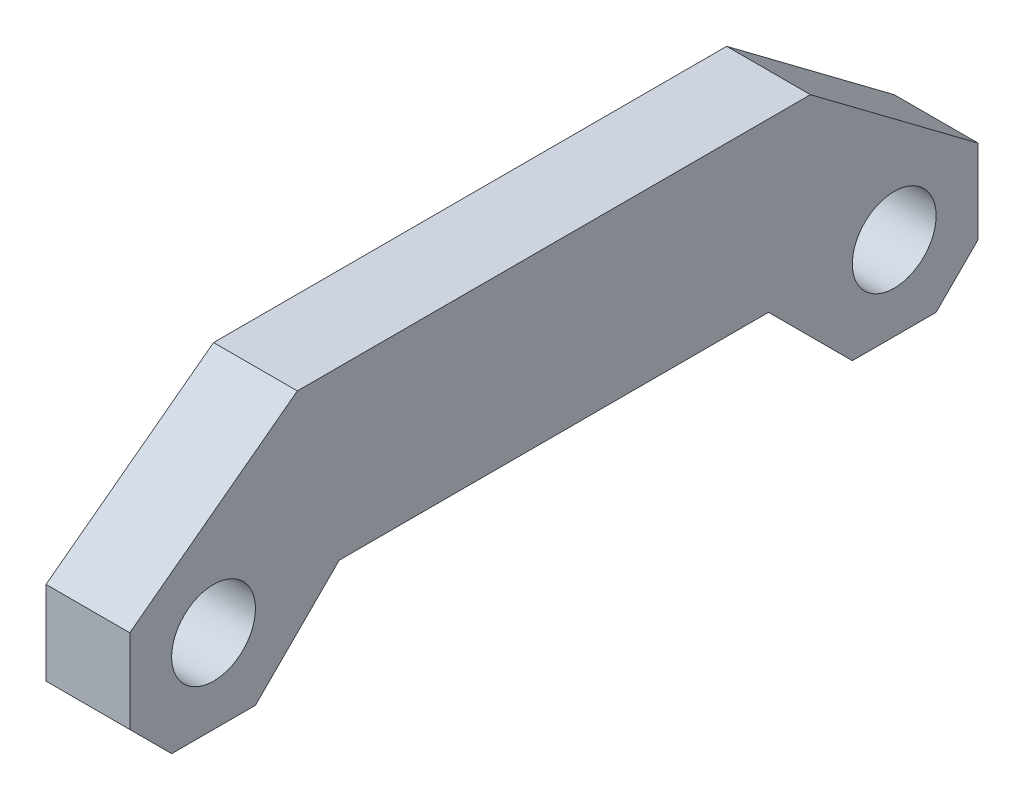
SolidWorks part; units mm, degrees
ref_plane "Front" through (0, 0, 0) normal (0, 0, 1) x (1, 0, 0)
ref_plane "Top" through (0, 0, 0) normal (0, 1, 0) x (1, 0, 0)
ref_plane "Right" through (0, 0, 0) normal (1, 0, 0) x (0, 0, -1)
sketch "Sketch1" plane through (0, 0, 0) normal (1, 0, 0) x (0, 0, -1)
  line L0 (-103.1875, 0) -> (103.1875, 0) construction
  line L1 (-128.5875, 50.8) -> (128.5875, 50.8)
  line L2 (-128.5875, 50.8) -> (-128.5875, -25.4)
  line L3 (-128.5875, -25.4) -> (128.5875, -25.4)
  line L4 (128.5875, 50.8) -> (128.5875, -25.4)
  line L5 (0, -25.4) -> (0, 50.8) construction
  circle A0 centre (-103.1875, 0) radius 12.7
  circle A1 centre (103.1875, 0) radius 12.7
  dimension "D5" = 25.4
  dimension "D1" = 25.4
  dimension "D2" = 76.2
  dimension "D3" = 206.375
  dimension "D4" = 25.4
extrude "Extrude1" add sketch "Sketch1" along normal mid plane 25.4
sketch "Sketch2" plane through (12.7, 0, 0) normal (1, 0, 0) x (0, 0, -1)
  line L0 (-90.4875, -25.4) -> (-65.0875, 0)
  line L1 (-128.5875, -25.4) -> (128.5875, -25.4) construction
  line L2 (-65.0875, 0) -> (65.0875, 0)
  line L3 (65.0875, 0) -> (90.4875, -25.4)
  line L4 (90.4875, -25.4) -> (-90.4875, -25.4)
  line L5 (0, -25.4) -> (0, 50.8) construction
  line L6 (128.5875, 50.8) -> (-128.5875, 50.8) construction
  line L7 (-128.5875, 50.8) -> (-128.5875, 12.7)
  line L8 (-128.5875, 50.8) -> (-128.5875, -25.4) construction
  line L9 (-128.5875, 12.7) -> (-77.7875, 50.8)
  line L10 (-77.7875, 50.8) -> (-128.5875, 50.8)
  line L11 (77.7875, 50.8) -> (128.5875, 50.8)
  line L12 (128.5875, 50.8) -> (128.5875, 12.7)
  line L13 (128.5875, -25.4) -> (128.5875, 50.8) construction
  line L14 (128.5875, 12.7) -> (77.7875, 50.8)
  line L15 (-128.5875, -25.4) -> (-128.5875, -12.7)
  line L16 (-128.5875, -12.7) -> (-115.8875, -25.4)
  line L17 (-115.8875, -25.4) -> (-128.5875, -25.4)
  line L19 (128.5875, -12.7) -> (128.5875, -25.4)
  line L20 (128.5875, -25.4) -> (115.8875, -25.4)
  line L21 (115.8875, -25.4) -> (128.5875, -12.7)
  dimension "D1" = 38.1
  dimension "D2" = 38.1
  dimension "D3" = 25.4
  dimension "D4" = 12.7
  dimension "D5" = 50.8
extrude "Cut-Extrude2" cut sketch "Sketch2" against normal up to next
